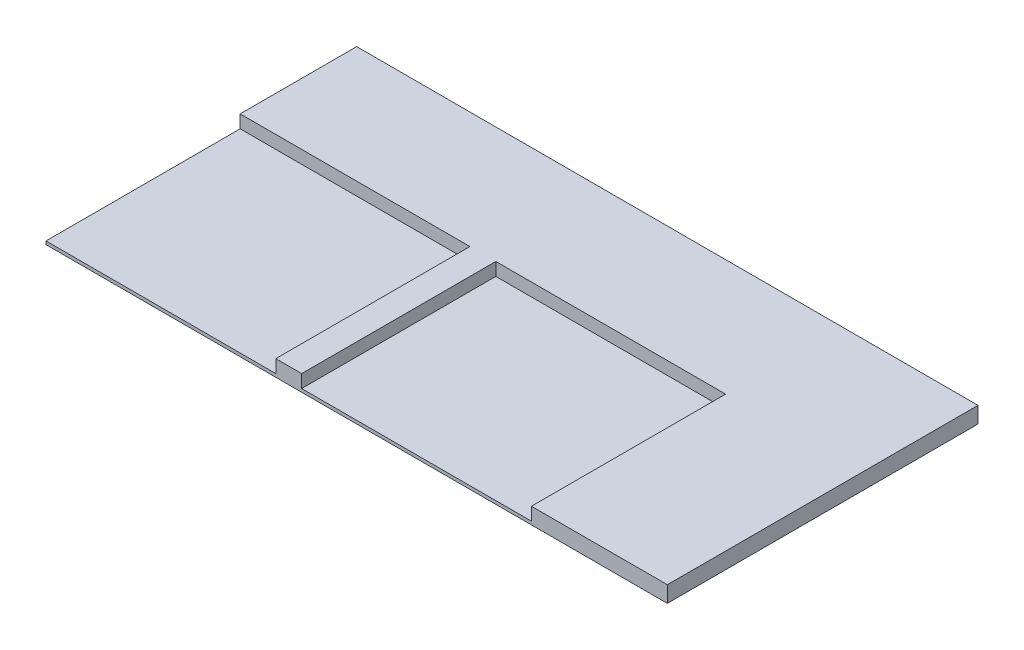
SolidWorks part; units mm, degrees
ref_plane "Front Plane" through (0, 0, 0) normal (0, 0, 1) x (1, 0, 0)
ref_plane "Top Plane" through (0, 0, 0) normal (0, 1, 0) x (1, 0, 0)
ref_plane "Right Plane" through (0, 0, 0) normal (1, 0, 0) x (0, 0, -1)
sketch "Sketch1" plane through (0, 0, 0) normal (0, 1, 0) x (1, 0, 0)
  line L1 (0, 0) -> (1219.2, 0)
  line L2 (0, 0) -> (0, 609.6)
  line L3 (0, 609.6) -> (1219.2, 609.6)
  line L4 (1219.2, 0) -> (1219.2, 609.6)
  dimension "D1" = 1219.2
  dimension "D2" = 609.6
extrude "Boss-Extrude1" add sketch "Sketch1" along normal blind 6.35
sketch "Sketch2" plane through (0, 6.35, 0) normal (0, 1, 0) x (1, 0, 0)
  line L0 (0, 0) -> (1219.2, 0) construction
  line L1 (0, 0) -> (450.85, 0)
  line L2 (0, 0) -> (0, 381)
  line L3 (0, 381) -> (450.85, 381)
  line L4 (450.85, 0) -> (450.85, 381)
  line L5 (501.65, 0) -> (952.5, 0)
  line L6 (501.65, 0) -> (501.65, 381)
  line L7 (501.65, 381) -> (952.5, 381)
  line L8 (952.5, 0) -> (952.5, 381)
  line L9 (0, 609.6) -> (1219.2, 609.6)
  line L10 (1219.2, 609.6) -> (1219.2, 0)
  line L11 (1219.2, 0) -> (952.5, 0)
  line L12 (952.5, 0) -> (952.5, 381)
  line L13 (952.5, 381) -> (501.65, 381)
  line L14 (501.65, 381) -> (501.65, 0)
  line L16 (450.85, 0) -> (450.85, 381)
  line L17 (450.85, 381) -> (0, 381)
  line L18 (0, 609.6) -> (0, 381)
  line L19 (0, 381) -> (450.85, 381)
  line L20 (450.85, 381) -> (450.85, 0)
  line L21 (450.85, 0) -> (501.65, 0)
  line L22 (501.65, 0) -> (501.65, 381)
  line L23 (501.65, 381) -> (952.5, 381)
  line L24 (952.5, 381) -> (952.5, 0)
  line L25 (952.5, 0) -> (1219.2, 0)
  line L26 (1219.2, 0) -> (1219.2, 609.6)
  line L27 (1219.2, 609.6) -> (0, 609.6)
  line L28 (450.85, 381) -> (501.65, 381)
  line L29 (450.85, 381) -> (450.85, 0)
  line L30 (450.85, 0) -> (501.65, 0)
  line L31 (501.65, 381) -> (501.65, 0)
  line L32 (0, 609.6) -> (1219.2, 609.6)
  line L33 (0, 609.6) -> (0, 381)
  line L34 (0, 381) -> (1219.2, 381)
  line L35 (1219.2, 609.6) -> (1219.2, 381)
  line L36 (952.5, 381) -> (1219.2, 381)
  line L37 (952.5, 381) -> (952.5, 0)
  line L38 (952.5, 0) -> (1219.2, 0)
  line L39 (1219.2, 381) -> (1219.2, 0)
  point P18 (0, 0)
  point P19 (0, 0)
  point P20 (0, 0)
  point P21 (501.65, 381)
  point P22 (0, 0)
  dimension "D1" = 450.85
  dimension "D2" = 381
  dimension "D3" = 450.85
  dimension "D5" = 50.8
sketch "Sketch7" plane through (0, 6.35, 0) normal (0, 1, 0) x (1, 0, 0)
  line L1 (0, 609.6) -> (1219.2, 609.6)
  line L2 (0, 609.6) -> (0, 381)
  line L3 (0, 381) -> (1219.2, 381)
  line L4 (1219.2, 609.6) -> (1219.2, 381)
  line L5 (952.5, 381) -> (1219.2, 381)
  line L6 (952.5, 381) -> (952.5, 0)
  line L7 (952.5, 0) -> (1219.2, 0)
  line L8 (1219.2, 381) -> (1219.2, 0)
  line L9 (450.85, 381) -> (501.65, 381)
  line L10 (450.85, 381) -> (450.85, 0)
  line L11 (450.85, 0) -> (501.65, 0)
  line L12 (501.65, 381) -> (501.65, 0)
extrude "Boss-Extrude2" add sketch "Sketch7" along normal blind 25.4 contours L2 L1 L4 L3 | L10 L9 L12 L11 | L6 L5 L8 L7
